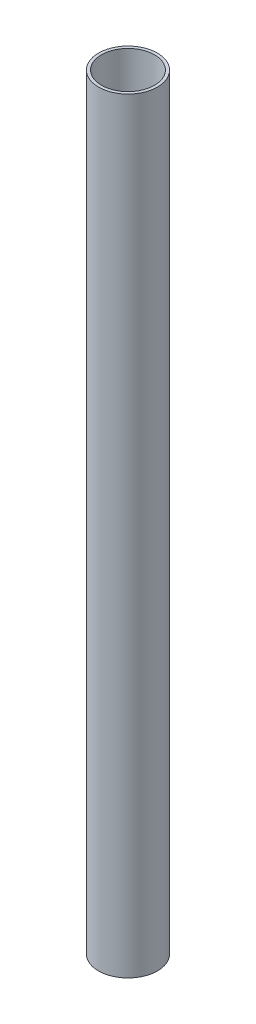
SolidWorks part; units mm, degrees
ref_plane "前视基准面" through (0, 0, 0) normal (0, 0, 1) x (1, 0, 0)
ref_plane "上视基准面" through (0, 0, 0) normal (0, 1, 0) x (1, 0, 0)
ref_plane "右视基准面" through (0, 0, 0) normal (1, 0, 0) x (0, 0, -1)
sketch "草图1" plane through (0, 0, 0) normal (0, 1, 0) x (1, 0, 0)
  circle A0 centre (0, 0) radius 10
  dimension "D1" = 20
extrude "1mm" add sketch "草图1" along normal mid plane 260 thin thin type one direction reverse wall 1
